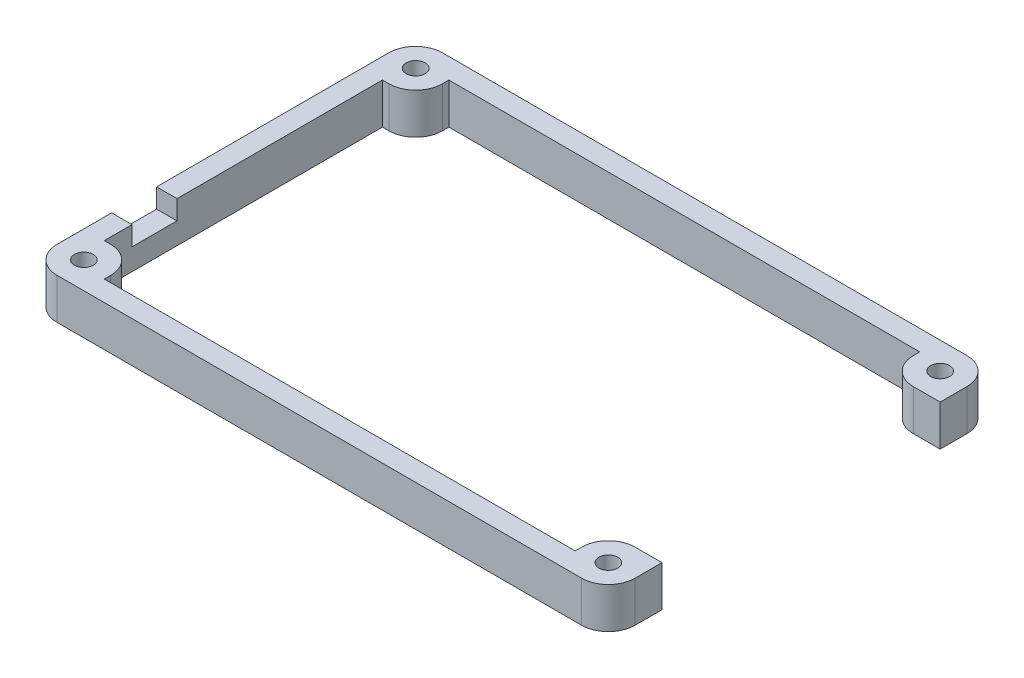
SolidWorks part; units mm, degrees
material "Rubber"
ref_plane "Front" through (0, 0, 0) normal (0, 0, 1) x (1, 0, 0)
ref_plane "Top" through (0, 0, 0) normal (0, 1, 0) x (1, 0, 0)
ref_plane "Right" through (0, 0, 0) normal (1, 0, 0) x (0, 0, -1)
sketch "Sketch1" plane through (0, 0, 0) normal (0, 1, 0) x (1, 0, 0)
  line L0 (-45, 0) -> (45, 0) construction
  line L1 (-45, 30) -> (45, 30) construction
  line L2 (-45, 30) -> (-45, -30) construction
  line L3 (-45, -30) -> (45, -30) construction
  line L4 (45, 30) -> (45, -30) construction
  line L5 (0, -30) -> (0, 30) construction
  line L6 (41.825, 26.825) -> (41.825, -26.825) construction
  line L7 (-41.825, -26.825) -> (41.825, -26.825) construction
  line L8 (-41.825, 26.825) -> (-41.825, -26.825) construction
  line L9 (-41.825, 26.825) -> (41.825, 26.825) construction
  line L10 (40.825, 25.825) -> (40.825, -25.825) construction
  line L11 (-40.825, -25.825) -> (40.825, -25.825) construction
  line L12 (-40.825, 25.825) -> (-40.825, -25.825) construction
  line L13 (-40.825, 25.825) -> (40.825, 25.825) construction
  line L14 (40.825, 21.65) -> (45, 21.65) construction
  line L15 (40.825, -21.65) -> (45, -21.65) construction
  line L16 (36.65, -25.825) -> (36.65, -30) construction
  line L17 (-36.65, -25.825) -> (-36.65, -30) construction
  line L18 (-40.825, -21.65) -> (-45, -21.65) construction
  line L19 (-36.65, 25.825) -> (-36.65, 30) construction
  line L20 (-40.825, 21.65) -> (-45, 21.65) construction
  line L21 (36.65, 25.825) -> (36.65, 30) construction
  line L22 (40.825, -25.825) -> (41.825, -25.825) construction
  circle A0 centre (-40.825, -25.825) radius 1 construction
  circle A1 centre (40.825, -25.825) radius 1 construction
  circle A2 centre (40.825, 25.825) radius 1 construction
  circle A3 centre (-40.825, 25.825) radius 1 construction
  circle A4 centre (40.825, -25.825) radius 4.175 construction
  circle A5 centre (40.825, 25.825) radius 4.175 construction
  circle A6 centre (-40.825, 25.825) radius 4.175 construction
  circle A7 centre (-40.825, -25.825) radius 4.175 construction
  dimension "D1" = 90
  dimension "D2" = 60
  dimension "D4" = 1
  dimension "D3" = 3.175
sketch "Sketch2" plane through (0, 0, 0) normal (0, 1, 0) x (1, 0, 0)
  line L0 (-45, 30) -> (-45, -30) construction
  line L1 (-45, -30) -> (45, -30) construction
  line L2 (45, 30) -> (45, -30) construction
  line L3 (-45, 30) -> (45, 30) construction
  line L4 (40.825, 21.65) -> (45, 21.65) construction
  line L5 (36.65, 25.825) -> (36.65, 30) construction
  line L6 (-36.65, 25.825) -> (-36.65, 30) construction
  line L7 (-40.825, 21.65) -> (-45, 21.65) construction
  line L8 (-36.65, -25.825) -> (-36.65, -30) construction
  line L9 (-40.825, -21.65) -> (-45, -21.65) construction
  line L10 (36.65, -25.825) -> (36.65, -30) construction
  line L11 (40.825, -21.65) -> (45, -21.65) construction
  line L16 (-45, 25.825) -> (-45, -25.825)
  line L17 (-40.825, -30) -> (40.825, -30)
  line L18 (45, 25.825) -> (45, -25.825)
  line L19 (-40.825, 30) -> (40.825, 30)
  line L20 (40.825, 21.65) -> (41.825, 21.65)
  line L21 (36.65, 25.825) -> (36.65, 26.825)
  line L22 (-36.65, 25.825) -> (-36.65, 26.825)
  line L23 (-40.825, 21.65) -> (-41.825, 21.65)
  line L24 (-36.65, -25.825) -> (-36.65, -26.825)
  line L25 (-40.825, -21.65) -> (-41.825, -21.65)
  line L26 (36.65, -25.825) -> (36.65, -26.825)
  line L27 (40.825, -21.65) -> (41.825, -21.65)
  line L28 (41.825, 26.825) -> (41.825, -26.825) construction
  line L29 (-36.65, -26.825) -> (36.65, -26.825)
  line L30 (-41.825, 26.825) -> (41.825, 26.825) construction
  line L31 (-41.825, 26.825) -> (-41.825, -26.825) construction
  line L32 (-36.65, 26.825) -> (36.65, 26.825)
  line L33 (-41.825, 21.65) -> (-41.825, -21.65)
  line L34 (41.825, 21.65) -> (41.825, -21.65)
  line L35 (-41.825, -26.825) -> (41.825, -26.825) construction
  circle A0 centre (40.825, 25.825) radius 4.175 construction
  circle A1 centre (40.825, 25.825) radius 1 construction
  circle A2 centre (-40.825, 25.825) radius 4.175 construction
  circle A3 centre (-40.825, 25.825) radius 1 construction
  circle A4 centre (-40.825, -25.825) radius 4.175 construction
  circle A5 centre (40.825, -25.825) radius 4.175 construction
  arc A6 (45, 25.825) -> (40.825, 30) centre (40.825, 25.825) ccw
  circle A7 centre (40.825, 25.825) radius 1 construction
  arc A8 (-40.825, 30) -> (-45, 25.825) centre (-40.825, 25.825) ccw
  circle A9 centre (-40.825, 25.825) radius 1 construction
  arc A10 (-36.65, -25.825) -> (-40.825, -21.65) centre (-40.825, -25.825) ccw
  arc A11 (40.825, -21.65) -> (36.65, -25.825) centre (40.825, -25.825) ccw
  circle A12 centre (-40.825, -25.825) radius 1 construction
  circle A13 centre (40.825, -25.825) radius 1 construction
  circle A14 centre (-40.825, -25.825) radius 1 construction
  circle A15 centre (40.825, -25.825) radius 1 construction
  arc A16 (-40.825, 21.65) -> (-36.65, 25.825) centre (-40.825, 25.825) ccw
  arc A17 (-45, -25.825) -> (-40.825, -30) centre (-40.825, -25.825) ccw
  arc A18 (40.825, -30) -> (45, -25.825) centre (40.825, -25.825) ccw
  arc A19 (36.65, 25.825) -> (40.825, 21.65) centre (40.825, 25.825) ccw
extrude "Boss-Extrude3" add sketch "Sketch2" along normal blind 6.35
sketch "Antenna Hole Size" plane through (-45, 0, 0) normal (-1, 0, 0) x (0, 0, 1)
  line L0 (13.825, 6.35) -> (25.825, 6.35) construction
  line L1 (25.825, 6.35) -> (25.825, 0) construction
  line L3 (10.325, 9.35) -> (17.325, 9.35)
  line L4 (10.325, 9.35) -> (10.325, 3.35)
  line L5 (10.325, 3.35) -> (17.325, 3.35)
  line L6 (17.325, 9.35) -> (17.325, 3.35)
  line L7 (10.325, 9.35) -> (17.325, 3.35) construction
  line L8 (10.325, 3.35) -> (17.325, 9.35) construction
  dimension "D1" = 12
  dimension "D2" = 6
  dimension "D3" = 7
extrude "Cut-Extrude3" cut sketch "Antenna Hole Size" against normal up to surface (3.175 mm away) up to face at (-41.825, 3.175, 0)
sketch "Sketch7" plane through (0, 0, 0) normal (0, -1, 0) x (1, 0, 0)
  circle A0 centre (-40.825, -25.825) radius 1.4732
  circle A1 centre (-40.825, 25.825) radius 1.4732
  circle A2 centre (40.825, 25.825) radius 1.4732
  circle A3 centre (40.825, -25.825) radius 1.4732
  dimension "D1" = 2.9464
  dimension "D2" = 2.9464
  dimension "D3" = 2.9464
  dimension "D4" = 2.9464
extrude "Cut-Extrude4" cut sketch "Sketch7" against normal blind 10
sketch "Sketch8" plane through (0, 6.35, 0) normal (0, 1, 0) x (1, 0, 0)
  line L0 (45, -25.825) -> (45, 25.825) construction
  line L1 (45, 21.65) -> (41.825, 21.65)
  line L2 (45, 21.65) -> (45, -21.65)
  line L3 (45, -21.65) -> (41.825, -21.65)
  line L4 (41.825, 21.65) -> (41.825, -21.65)
  line L5 (45, 21.65) -> (41.825, -21.65) construction
  line L6 (45, -21.65) -> (41.825, 21.65) construction
  point P0 (43.4125, 0)
extrude "Cut-Extrude5" cut sketch "Sketch8" against normal through all
sketch "Sketch9" plane through (-45, 0, 0) normal (-1, 0, 0) x (0, 0, 1)
  line L0 (10.325, 6.35) -> (17.325, 6.35) construction
  line L1 (13.825, 6.35) -> (13.825, 3.35) construction
  line L2 (10.325, 3.35) -> (17.325, 3.35) construction
